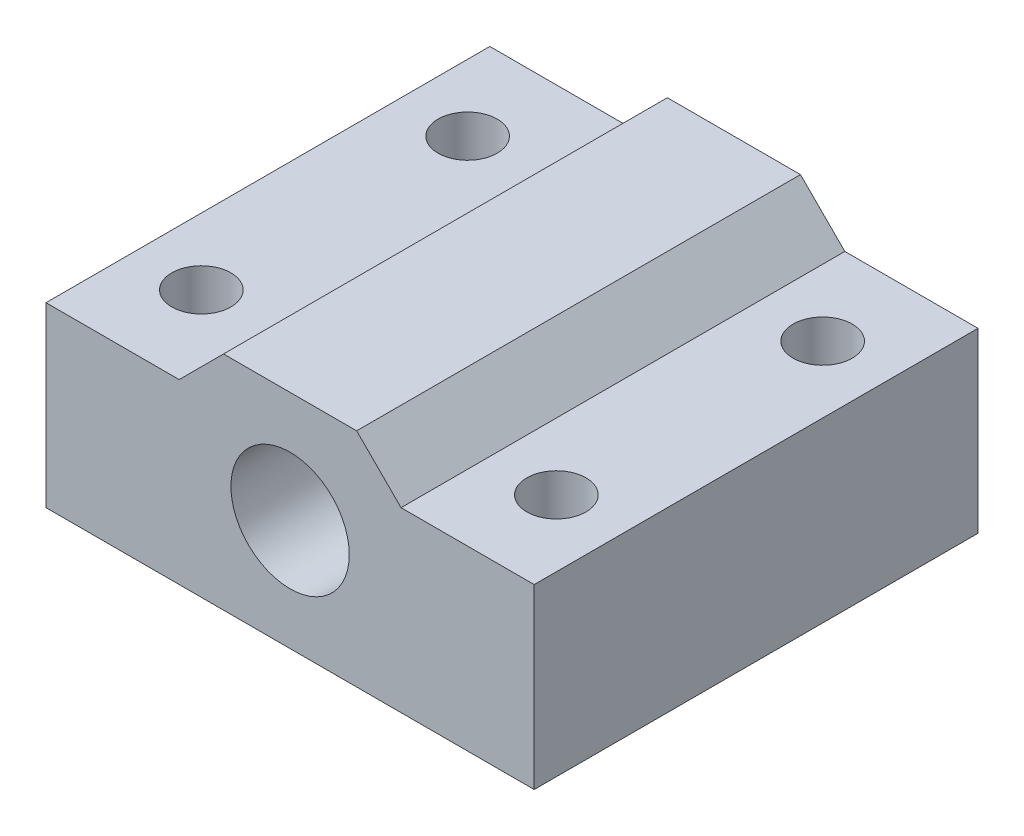
SolidWorks part; units mm, degrees
material "Alliage 1060"
ref_plane "Plan de face" through (0, 0, 0) normal (0, 0, 1) x (1, 0, 0)
ref_plane "Plan de dessus" through (0, 0, 0) normal (0, 1, 0) x (1, 0, 0)
ref_plane "Plan de droite" through (0, 0, 0) normal (1, 0, 0) x (0, 0, -1)
sketch "Esquisse1" plane through (0, 0, 0) normal (0, 1, 0) x (1, 0, 0)
  line L1 (16.5, 15) -> (-16.5, 15)
  line L2 (16.5, 15) -> (16.5, -15)
  line L3 (16.5, -15) -> (-16.5, -15)
  line L4 (-16.5, 15) -> (-16.5, -15)
  line L5 (16.5, 15) -> (-16.5, -15) construction
  line L6 (16.5, -15) -> (-16.5, 15) construction
  point P0 (0, 0)
  dimension "D1" = 30
  dimension "D2" = 33
extrude "Boss.-Extru.1" add sketch "Esquisse1" along normal blind 15
sketch "Esquisse2" plane through (0, 0, 15) normal (0, 0, 1) x (1, 0, 0)
  line L0 (-16.5, 0) -> (16.5, 0) construction
  circle A0 centre (0, 7.5) radius 4
  dimension "D1" = 8
  dimension "D2" = 7.5
extrude "Enlèv. mat.-Extru.1" cut sketch "Esquisse2" against normal through all
sketch "Esquisse3" plane through (0, 0, 15) normal (0, 0, 1) x (1, 0, 0)
  line L0 (-16.5, 15) -> (-16.5, 12)
  line L1 (-16.5, 15) -> (16.5, 15) construction
  line L2 (-16.5, 15) -> (-16.5, 0) construction
  line L3 (-16.5, 12) -> (-7.5, 12)
  line L4 (-7.5, 12) -> (-4.5, 15)
  line L5 (-4.5, 15) -> (-16.5, 15)
  dimension "D1" = 135
  dimension "D2" = 3
  dimension "D3" = 9
extrude "Enlèv. mat.-Extru.2" cut sketch "Esquisse3" against normal through all
mirror "Symétrie1" about plane through (0, 0, 0) normal (1, 0, 0) of "Enlèv. mat.-Extru.2"
sketch "Esquisse4" plane through (0, 12, 0) normal (0, 1, 0) x (1, 0, 0)
  line L0 (-12, 9) -> (12, 9) construction
  line L1 (12, 9) -> (12, -9) construction
  line L2 (12, -9) -> (-12, -9) construction
  line L3 (-12, -9) -> (-12, 9) construction
  circle A0 centre (-12, 9) radius 2
  circle A1 centre (12, 9) radius 2
  circle A2 centre (-12, -9) radius 2
  circle A3 centre (12, -9) radius 2
  point P9 (0, 9)
  point P10 (-12, 0)
  dimension "D1" = 4
  dimension "D2" = 24
  dimension "D3" = 18
extrude "Enlèv. mat.-Extru.3" cut sketch "Esquisse4" against normal through all
